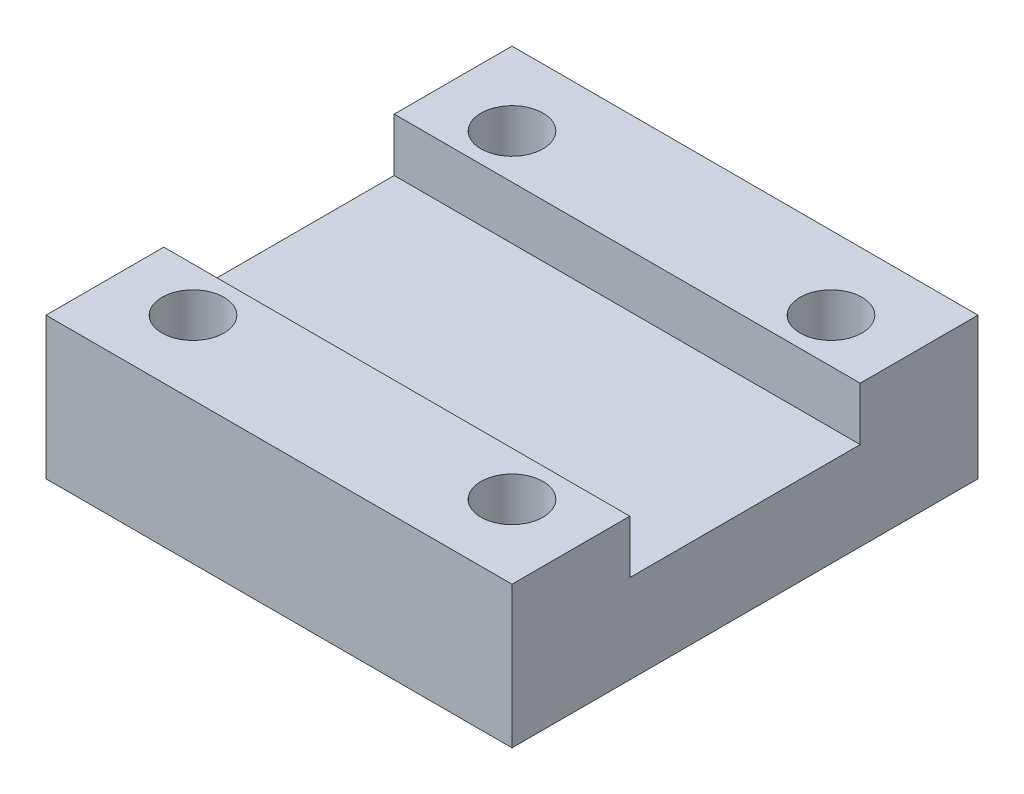
SolidWorks part; units mm, degrees
ref_plane "Front Plane" through (0, 0, 0) normal (0, 0, 1) x (1, 0, 0)
ref_plane "Top Plane" through (0, 0, 0) normal (0, 1, 0) x (1, 0, 0)
ref_plane "Right Plane" through (0, 0, 0) normal (1, 0, 0) x (0, 0, -1)
sketch "Sketch1" plane through (0, 0, 0) normal (0, 1, 0) x (1, 0, 0)
  line L1 (-26.295, -26.295) -> (26.295, -26.295)
  line L2 (-26.295, -26.295) -> (-26.295, 26.295)
  line L3 (-26.295, 26.295) -> (26.295, 26.295)
  line L4 (26.295, -26.295) -> (26.295, 26.295)
  line L5 (-26.295, -26.295) -> (26.295, 26.295) construction
  line L6 (-26.295, 26.295) -> (26.295, -26.295) construction
  point P0 (0, 0)
  dimension "D1" = 52.59
extrude "Boss-Extrude1" add sketch "Sketch1" along normal blind 16
sketch "Sketch2" plane through (26.295, 0, 0) normal (1, 0, 0) x (0, 0, -1)
  line L0 (-26.295, 16) -> (26.295, 16) construction
  line L1 (-13, 16) -> (13, 16)
  line L2 (-13, 16) -> (-13, 10)
  line L3 (-13, 10) -> (13, 10)
  line L4 (13, 16) -> (13, 10)
  point P6 (0, 16)
  point P7 (0, 16)
  dimension "D1" = 26
  dimension "D2" = 6
extrude "Cut-Extrude1" cut sketch "Sketch2" against normal through all
sketch "Sketch3" plane through (0, 16, 0) normal (0, 1, 0) x (1, 0, 0)
  line L0 (-26.295, 13) -> (26.295, 13) construction
  line L1 (-18, -18) -> (18, -18) construction
  line L2 (-18, -18) -> (-18, 18) construction
  line L3 (-18, 18) -> (18, 18) construction
  line L4 (18, -18) -> (18, 18) construction
  line L5 (-18, -18) -> (18, 18) construction
  line L6 (-18, 18) -> (18, -18) construction
  line L9 (-11.5842, 18) -> (-14.7921, 23.5562) construction
  line L10 (-14.7921, 23.5562) -> (-21.2079, 23.5562) construction
  line L11 (-21.2079, 23.5562) -> (-24.4158, 18) construction
  line L12 (-24.4158, 18) -> (-21.2079, 12.4437) construction
  line L13 (-21.2079, 12.4437) -> (-14.7921, 12.4437) construction
  line L15 (-14.7921, 12.4437) -> (-11.5842, 18) construction
  line L16 (-26.295, 26.295) -> (-26.295, 13) construction
  circle A0 centre (-18, 18) radius 3.5
  circle A1 centre (18, 18) radius 3.5
  circle A2 centre (18, -18) radius 3.5
  circle A3 centre (-18, -18) radius 3.5
  circle A4 centre (-18, 18) radius 5.5563 construction
  point P0 (0, 0)
  point P12 (0, 0)
  dimension "D1" = 7
  dimension "D5" = 4.795
  dimension "D2" = 1.5
  dimension "D3" = 11.1125
  dimension "D4" = 1.8792
  dimension "D6" = 36
extrude "Cut-Extrude2" cut sketch "Sketch3" against normal through all
sketch "Sketch4" plane through (0, 0, 0) normal (0, -1, 0) x (1, 0, 0)
  line L1 (-14.6802, -12.25) -> (-21.3198, -12.25)
  line L2 (-21.3198, -12.25) -> (-24.6395, -18)
  line L3 (-24.6395, -18) -> (-21.3198, -23.75)
  line L4 (-21.3198, -23.75) -> (-14.6802, -23.75)
  line L5 (-14.6802, -23.75) -> (-11.3605, -18)
  line L6 (-11.3605, -18) -> (-14.6802, -12.25)
  line L7 (-11.3605, 18) -> (-14.6802, 23.75)
  line L8 (-14.6802, 23.75) -> (-21.3198, 23.75)
  line L9 (-21.3198, 23.75) -> (-24.6395, 18)
  line L10 (-24.6395, 18) -> (-21.3198, 12.25)
  line L11 (-21.3198, 12.25) -> (-14.6802, 12.25)
  line L12 (-14.6802, 12.25) -> (-11.3605, 18)
  line L13 (21.3198, 12.25) -> (24.6395, 18)
  line L14 (24.6395, 18) -> (21.3198, 23.75)
  line L15 (21.3198, 23.75) -> (14.6802, 23.75)
  line L16 (14.6802, 23.75) -> (11.3605, 18)
  line L17 (11.3605, 18) -> (14.6802, 12.25)
  line L18 (14.6802, 12.25) -> (21.3198, 12.25)
  line L19 (21.3198, -23.75) -> (24.6395, -18)
  line L20 (24.6395, -18) -> (21.3198, -12.25)
  line L21 (21.3198, -12.25) -> (14.6802, -12.25)
  line L22 (14.6802, -12.25) -> (11.3605, -18)
  line L23 (11.3605, -18) -> (14.6802, -23.75)
  line L24 (14.6802, -23.75) -> (21.3198, -23.75)
  circle A0 centre (-18, -18) radius 5.75 construction
  circle A1 centre (-18, 18) radius 5.75 construction
  circle A2 centre (18, 18) radius 5.75 construction
  circle A3 centre (18, -18) radius 5.75 construction
  dimension "D1" = 11.5
extrude "Cut-Extrude3" [suppressed] cut sketch "Sketch4" against normal blind 5.5
equation "\"D1@Sketch1\"=25.4+1.5*4+6.36+12.83+2"
